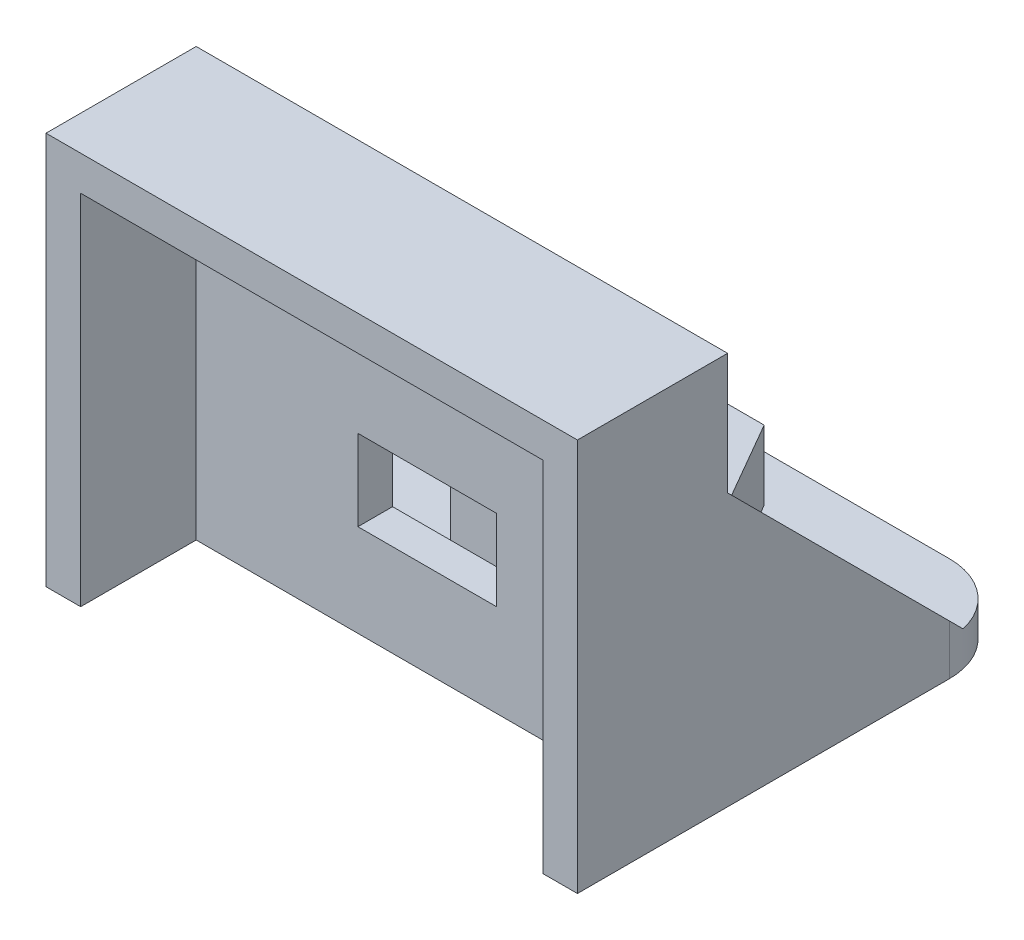
SolidWorks part; units mm, degrees
ref_plane "前视基准面" through (0, 0, 0) normal (0, 0, 1) x (1, 0, 0)
ref_plane "上视基准面" through (0, 0, 0) normal (0, 1, 0) x (1, 0, 0)
ref_plane "右视基准面" through (0, 0, 0) normal (1, 0, 0) x (0, 0, -1)
sketch "草图1" plane through (0, 0, 0) normal (0, 0, 1) x (1, 0, 0)
  line L1 (-11.5, 8.5) -> (11.5, 8.5)
  line L2 (-11.5, 8.5) -> (-11.5, -8.5)
  line L3 (-11.5, -8.5) -> (11.5, -8.5)
  line L4 (11.5, 8.5) -> (11.5, -8.5)
  line L5 (-11.5, 8.5) -> (11.5, -8.5) construction
  line L6 (-11.5, -8.5) -> (11.5, 8.5) construction
  point P0 (0, 0)
  dimension "D1" = 23
  dimension "D2" = 17
extrude "凸台-拉伸1" add sketch "草图1" along normal blind 6.5
sketch "草图2" plane through (0, 0, 6.5) normal (0, 0, 1) x (1, 0, 0)
  line L0 (0, -3.575) -> (0, 3.575) construction
  line L1 (-10, 7) -> (10, 7)
  line L2 (-10, 7) -> (-10, -8.5)
  line L3 (-10, -8.5) -> (10, -8.5)
  line L4 (10, 7) -> (10, -8.5)
  line L5 (-10, 7) -> (10, -8.5) construction
  line L6 (-10, -8.5) -> (10, 7) construction
  line L7 (-11.5, -8.5) -> (11.5, -8.5) construction
  line L8 (11.5, 8.5) -> (-11.5, 8.5) construction
  line L9 (-11.5, 8.5) -> (-11.5, -8.5) construction
  line L10 (11.5, -8.5) -> (11.5, 8.5) construction
  point P0 (0, -0.75)
  dimension "D1" = 1.5
  dimension "D2" = 1.5
  dimension "D3" = 1.5
extrude "切除-拉伸1" cut sketch "草图2" against normal blind 5
sketch "草图3" plane through (0, 0, 0) normal (0, 0, -1) x (-1, 0, 0)
  line L0 (-11.5, -8.5) -> (-11.5, 8.5) construction
  line L1 (-11.5, -7) -> (11.5, -7)
  line L2 (-11.5, -7) -> (-11.5, -8.5)
  line L3 (-11.5, -8.5) -> (11.5, -8.5)
  line L4 (11.5, -7) -> (11.5, -8.5)
  dimension "D1" = 1.5
extrude "凸台-拉伸2" add sketch "草图3" along normal blind 12.6
sketch "草图4" plane through (0, -7, 0) normal (0, 1, 0) x (1, 0, 0)
  line L0 (4.9652, 6.3) -> (2.4826, 10.6)
  line L1 (3.2332, 6.3) -> (1.6166, 9.1)
  line L2 (1.6166, 9.1) -> (-1.6166, 9.1)
  line L3 (-1.6166, 9.1) -> (-3.2332, 6.3)
  line L4 (-3.2332, 6.3) -> (-1.6166, 3.5)
  line L5 (-1.6166, 3.5) -> (1.6166, 3.5)
  line L6 (1.6166, 3.5) -> (3.2332, 6.3)
  line L7 (2.4826, 10.6) -> (-2.4826, 10.6)
  line L8 (-2.4826, 10.6) -> (-4.9652, 6.3)
  line L9 (-4.9652, 6.3) -> (-2.4826, 2)
  line L10 (-2.4826, 2) -> (2.4826, 2)
  line L11 (2.4826, 2) -> (4.9652, 6.3)
  line L12 (0, -9.35) -> (0, 9.35) construction
  line L13 (-11.5, 0) -> (11.5, 0) construction
  line L14 (-11.5, 12.6) -> (11.5, 12.6) construction
  circle A0 centre (0, 6.3) radius 2.8 construction
  dimension "D1" = 5.6
  dimension "D3" = 2
  dimension "D4" = 2
  dimension "D2" = 1.5
extrude "凸台-拉伸3" add sketch "草图4" along normal blind 3
ref_plane "基准面4" through (0, -3.5, -3.5) normal (0, -0.7071, -0.7071) x (-1, 0, 0)
sketch "草图7" plane through (0, -3.5, -3.5) normal (0, -0.7071, -0.7071) x (-1, 0, 0)
  line L0 (-11.5, -10.6066) -> (-11.5, 2.8991) construction
  line L1 (-10, -4.9497) -> (-11.5, -4.9497)
  line L2 (-10, -4.9497) -> (-10, 2.3101)
  line L3 (-10, 2.3101) -> (-11.5, 2.3101)
  line L4 (-11.5, -4.9497) -> (-11.5, 2.3101)
  line L5 (11.5, -4.9497) -> (-11.5, -4.9497) construction
  dimension "D1" = 1.5
extrude "凸台-拉伸6" add sketch "草图7" along normal up to surface and the other way up to surface up to face at (0, -7, -6.3) other way up to face at (0, 0.75, 0)
mirror "镜向1" about plane through (0, 0, 0) normal (1, 0, 0) of "凸台-拉伸6"
hole_wizard "M3 间隙孔1" positions "草图8" profile "草图9" hole size "M3" standard "ISO" end condition up to next
sketch "草图8" plane through (0, -7, 0) normal (0, 1, 0) x (1, 0, 0)
  point P0 (0, 6.3)
sketch "草图9" plane through (0, -7, -6.3) normal (1, 0, 0) x (0, 0, 1)
  line L0 (0, 0) -> (0, 1.5)
  line L1 (0, 1.5) -> (1.6, 1.5)
  line L2 (1.6, 1.5) -> (1.6, 0)
  line L5 (1.6, 0) -> (0, 0)
  line L11 (0, -6.35) -> (0, 107.95) construction
  dimension "通孔孔直径" = 3.2
  dimension "通孔孔深度" = 1.5
fillet "圆角1" radius 3 2 edges at (-11.5, -7.75, -12.6) (11.5, -7.75, -12.6)
sketch "草图10" plane through (0, 0, 0) normal (0, 0, -1) x (-1, 0, 0)
  line L1 (-3, -1) -> (3, -1)
  line L2 (-3, -1) -> (-3, -4.5)
  line L3 (-3, -4.5) -> (3, -4.5)
  line L4 (3, -1) -> (3, -4.5)
  point P4 (0, 0)
  point P5 (0, 0)
  point P6 (0, 0)
  point P8 (0, 0)
  point P9 (0, 0)
extrude "切除-拉伸2" cut sketch "草图10" against normal up to next
